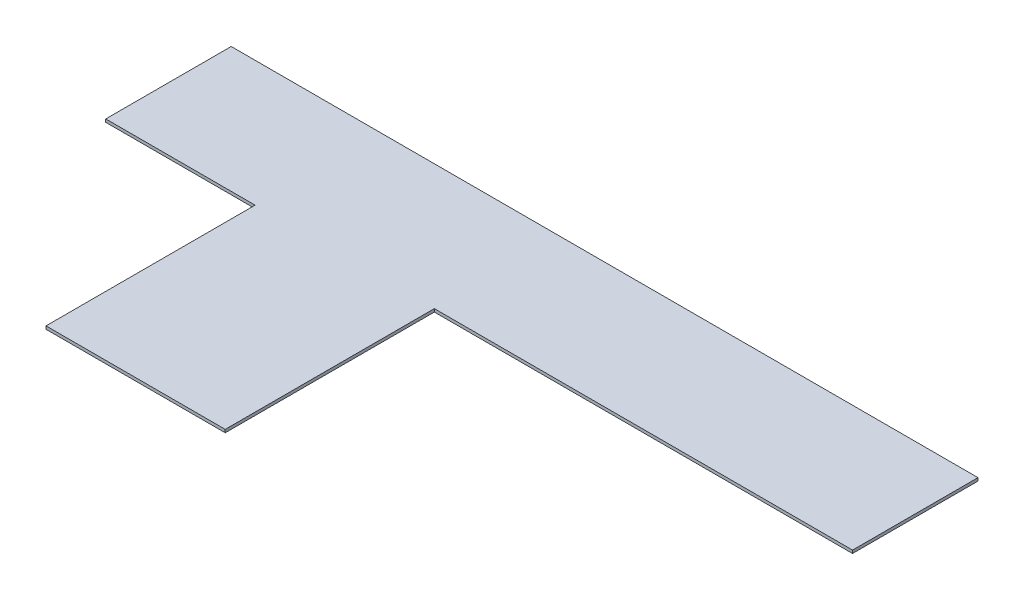
SolidWorks part; units mm, degrees
ref_plane "Front Plane" through (0, 0, 0) normal (0, 0, 1) x (1, 0, 0)
ref_plane "Top Plane" through (0, 0, 0) normal (0, 1, 0) x (1, 0, 0)
ref_plane "Right Plane" through (0, 0, 0) normal (1, 0, 0) x (0, 0, -1)
sketch "Sketch1" plane through (0, 0, 0) normal (0, 1, 0) x (1, 0, 0)
  line L1 (-6411.9171, 2389.8964) -> (6088.0829, 2389.8964)
  line L2 (-6411.9171, 2389.8964) -> (-6411.9171, 289.8964)
  line L3 (-6411.9171, 289.8964) -> (6088.0829, 289.8964)
  line L4 (6088.0829, 2389.8964) -> (6088.0829, 289.8964)
  line L5 (-6411.9171, 2389.8964) -> (6088.0829, 289.8964) construction
  line L6 (-6411.9171, 289.8964) -> (6088.0829, 2389.8964) construction
  line L7 (-3911.9171, 289.8964) -> (-911.9171, 289.8964)
  line L8 (-3911.9171, 289.8964) -> (-3911.9171, -3210.1036)
  line L9 (-3911.9171, -3210.1036) -> (-911.9171, -3210.1036)
  line L10 (-911.9171, 289.8964) -> (-911.9171, -3210.1036)
  line L11 (-3911.9171, 289.8964) -> (-911.9171, -3210.1036) construction
  line L12 (-3911.9171, -3210.1036) -> (-911.9171, 289.8964) construction
  point P4 (-161.9171, 1339.8964)
  point P9 (-2411.9171, -1460.1036)
  dimension "D1" = 12500
  dimension "D2" = 7000
  dimension "D3" = 3500
  dimension "D4" = 3000
  dimension "D5" = 2100
extrude "Boss-Extrude1" add sketch "Sketch1" along normal blind 50 contours L4 L1 L2 L3 | L10 L3 L8 L9
sketch "Sketch2" plane through (0, 0, 0) normal (0, -1, 0) x (1, 0, 0)
  line L0 (-2411.9171, 3210.1036) -> (-2411.9171, -3162.0775) construction
  line L1 (-3911.9171, 3210.1036) -> (-911.9171, 3210.1036) construction
  line L2 (-3911.9171, 1460.1036) -> (-911.9171, 1460.1036) construction
  line L3 (-3911.9171, -289.8964) -> (-3911.9171, 3210.1036) construction
  line L4 (-911.9171, -289.8964) -> (-911.9171, 3210.1036) construction
  line L5 (-6411.9171, -1339.8964) -> (6088.0829, -1339.8964) construction
  line L6 (-2036.9171, 1085.1036) -> (-2786.9171, 1085.1036)
  line L7 (-2036.9171, 1085.1036) -> (-2036.9171, 1835.1036)
  line L8 (-2036.9171, 1835.1036) -> (-2786.9171, 1835.1036)
  line L9 (-2786.9171, 1085.1036) -> (-2786.9171, 1835.1036)
  line L10 (-2036.9171, 1085.1036) -> (-2786.9171, 1835.1036) construction
  line L11 (-2036.9171, 1835.1036) -> (-2786.9171, 1085.1036) construction
  line L12 (-6411.9171, -2389.8964) -> (-6411.9171, -289.8964) construction
  line L13 (6088.0829, -2389.8964) -> (6088.0829, -289.8964) construction
  line L14 (-3286.9171, -289.8964) -> (-3286.9171, -2389.8964) construction
  line L15 (-6411.9171, -289.8964) -> (-3911.9171, -289.8964) construction
  line L16 (-6411.9171, -2389.8964) -> (6088.0829, -2389.8964) construction
  line L17 (2963.0829, -289.8964) -> (2963.0829, -2389.8964) construction
  line L18 (-911.9171, -289.8964) -> (6088.0829, -289.8964) construction
  line L19 (-161.9171, -289.8964) -> (-161.9171, -2389.8964) construction
  line L21 (-2911.9171, -1714.8964) -> (-3661.9171, -1714.8964)
  line L22 (-2911.9171, -1714.8964) -> (-2911.9171, -964.8964)
  line L23 (-2911.9171, -964.8964) -> (-3661.9171, -964.8964)
  line L24 (-3661.9171, -1714.8964) -> (-3661.9171, -964.8964)
  line L25 (-2911.9171, -1714.8964) -> (-3661.9171, -964.8964) construction
  line L26 (-2911.9171, -964.8964) -> (-3661.9171, -1714.8964) construction
  line L27 (213.0829, -1714.8964) -> (-536.9171, -1714.8964)
  line L28 (213.0829, -1714.8964) -> (213.0829, -964.8964)
  line L29 (213.0829, -964.8964) -> (-536.9171, -964.8964)
  line L30 (-536.9171, -1714.8964) -> (-536.9171, -964.8964)
  line L31 (213.0829, -1714.8964) -> (-536.9171, -964.8964) construction
  line L32 (213.0829, -964.8964) -> (-536.9171, -1714.8964) construction
  line L33 (3338.0829, -1714.8964) -> (2588.0829, -1714.8964)
  line L34 (3338.0829, -1714.8964) -> (3338.0829, -964.8964)
  line L35 (3338.0829, -964.8964) -> (2588.0829, -964.8964)
  line L36 (2588.0829, -1714.8964) -> (2588.0829, -964.8964)
  line L37 (3338.0829, -1714.8964) -> (2588.0829, -964.8964) construction
  line L38 (3338.0829, -964.8964) -> (2588.0829, -1714.8964) construction
  point P10 (-2411.9171, 1460.1036)
  point P34 (-3286.9171, -1339.8964)
  point P39 (-161.9171, -1339.8964)
  point P44 (2963.0829, -1339.8964)
  dimension "D1" = 750
  dimension "D2" = 750
  dimension "D3" = 3125
  dimension "D4" = 3125
  dimension "D5" = 6250
  dimension "D6" = 3125
  dimension "D7" = 750
  dimension "D8" = 750
extrude "Cut-Extrude1" cut sketch "Sketch2" against normal blind 10
